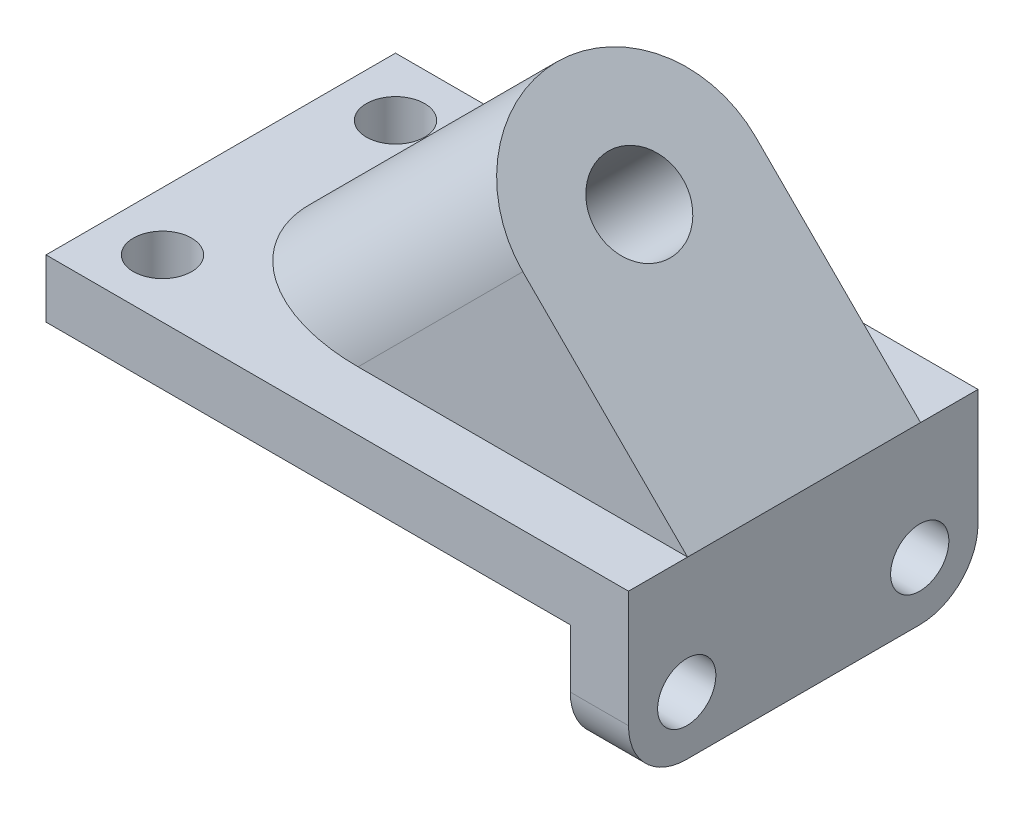
SolidWorks part; units mm, degrees
ref_plane "Front Plane" through (0, 0, 0) normal (0, 0, 1) x (1, 0, 0)
ref_plane "Top Plane" through (0, 0, 0) normal (0, 1, 0) x (1, 0, 0)
ref_plane "Right Plane" through (0, 0, 0) normal (1, 0, 0) x (0, 0, -1)
sketch "Sketch1" plane through (0, 0, 0) normal (0, 1, 0) x (1, 0, 0)
  line L0 (0, 0) -> (127, 0)
  line L1 (127, 0) -> (127, 76.2)
  line L2 (127, 76.2) -> (0, 76.2)
  line L3 (0, 76.2) -> (0, 0)
extrude "Boss-Extrude1" add sketch "Sketch1" along normal blind 12.7
sketch "Sketch2" plane through (0, 12.7, 0) normal (0, 1, 0) x (1, 0, 0)
  line L0 (0, 0) -> (127, 0) construction
  line L1 (127, 76.2) -> (114.3, 76.2)
  line L2 (127, 76.2) -> (127, 0)
  line L3 (127, 0) -> (114.3, 0)
  line L4 (114.3, 76.2) -> (114.3, 0)
extrude "Boss-Extrude2" add sketch "Sketch2" against normal blind 38.1
sketch "Sketch5" plane through (0, 12.7, 0) normal (0, 1, 0) x (1, 0, 0)
  circle A0 centre (12.7, 63.5) radius 6.35
  circle A1 centre (12.7, 12.7) radius 6.35
  point P0 (0, 0)
  dimension "D1" = 12.7
fillet "Fillet1" radius 12.7 1 edges at (120.65, -25.4, 0)
fillet "Fillet2" radius 12.7 1 edges at (120.65, -25.4, -76.2)
ref_plane "Plane1" through (69.85, 69.85, 0) normal (0.7071, 0.7071, 0) x (0, 0, -1)
sketch "Sketch7" plane through (69.85, 69.85, 0) normal (0.7071, 0.7071, 0) x (0, 0, -1)
  line L0 (63.6781, -80.8223) -> (12.8781, -80.8223)
  line L1 (0, -80.8223) -> (76.2, -80.8223) construction
  line L2 (12.8781, -80.8223) -> (12.8781, -30.0223)
  line L3 (63.6781, -80.8223) -> (63.6781, -30.0223)
  arc A0 (12.8781, -30.0223) -> (63.6781, -30.0223) centre (38.2781, -30.0223) cw
  circle A1 centre (38.2781, -30.0223) radius 9.525
  point P9 (0, 0)
  dimension "D4" = 19.05
  dimension "D1" = 50.8
  dimension "D2" = 50.8
  dimension "D3" = 12.5219
extrude "Boss-Extrude3" add sketch "Sketch7" against normal up to surface up to face at (63.5, 12.7, -38.1)
extrude "Cut-Extrude1" cut sketch "Sketch5" against normal blind 38.1
sketch "Sketch8" plane through (127, 0, 0) normal (1, 0, 0) x (0, 0, -1)
  circle A0 centre (12.7, -12.7) radius 6.35
  circle A1 centre (63.5, -12.7) radius 6.35
  point P0 (0, 0)
extrude "Cut-Extrude2" cut sketch "Sketch8" against normal blind 38.1
